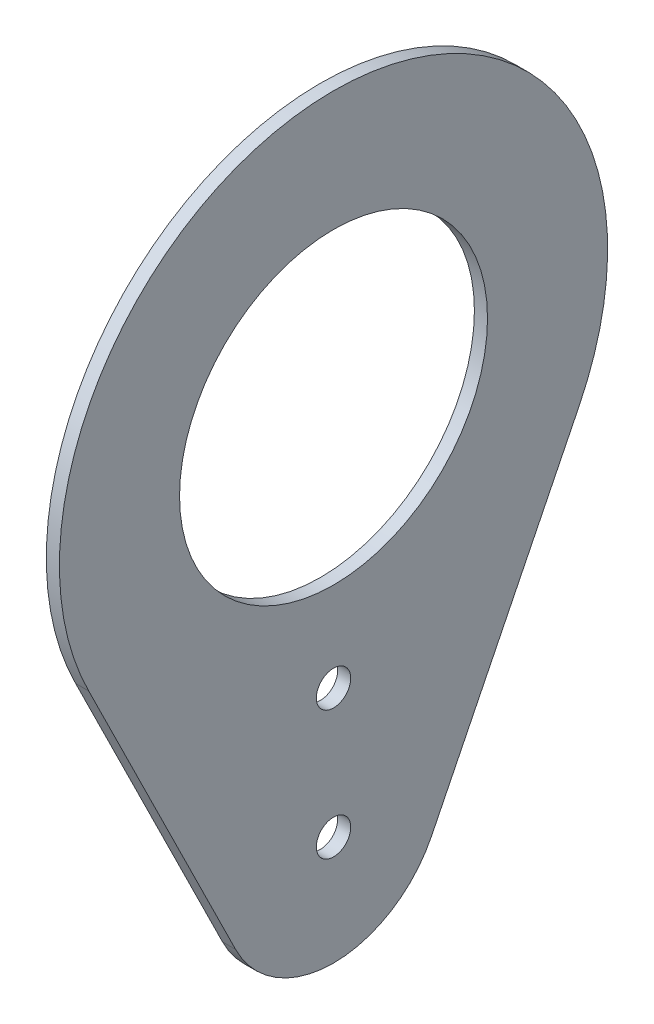
SolidWorks part; units mm, degrees
material "Thornel Mat VMA"
ref_plane "Front Plane" through (0, 0, 0) normal (0, 0, 1) x (1, 0, 0)
ref_plane "Top Plane" through (0, 0, 0) normal (0, 1, 0) x (1, 0, 0)
ref_plane "Right Plane" through (0, 0, 0) normal (1, 0, 0) x (0, 0, -1)
sketch "Sketch3" plane through (0, 0, 0) normal (1, 0, 0) x (0, 0, -1)
  line L0 (0, 0) -> (0, -43.28) construction
  line L1 (28.5763, -14.1214) -> (11.3855, -48.9067)
  line L2 (-28.4642, -14.346) -> (-11.3857, -48.9064)
  circle A0 centre (0, 0) radius 17.907
  circle A2 centre (0, -28.28) radius 2
  circle A3 centre (0, -43.28) radius 2
  arc A4 (-11.3857, -48.9064) -> (11.3855, -48.9067) centre (0, -43.28) ccw
  arc A5 (28.5763, -14.1214) -> (-28.4642, -14.346) centre (0, 0) ccw
  dimension "D1" = 35.814
  dimension "D2" = 28.28
  dimension "D4" = 4
  dimension "D5" = 15
  dimension "D6" = 25.4
extrude "Boss-Extrude2" add sketch "Sketch3" along normal blind 1.524
